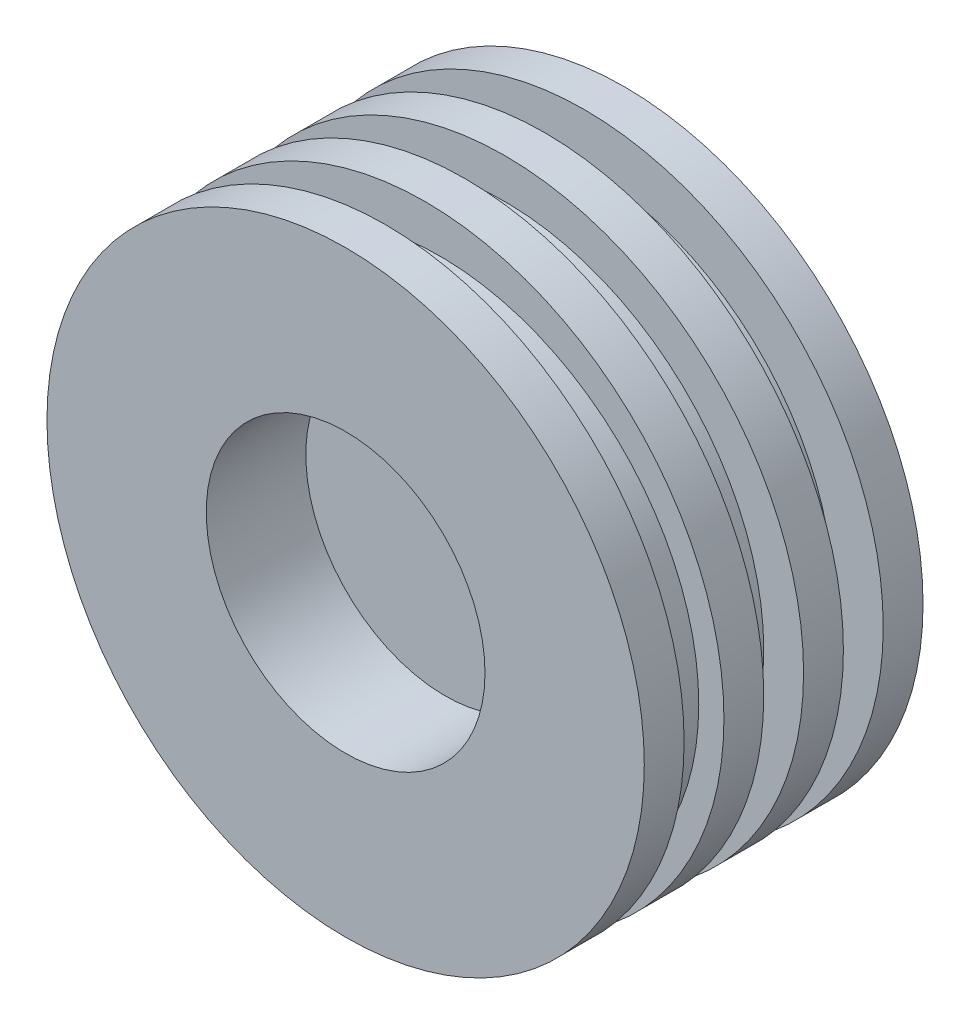
SolidWorks part; units mm, degrees
ref_plane "前视基准面" through (0, 0, 0) normal (0, 0, 1) x (1, 0, 0)
ref_plane "上视基准面" through (0, 0, 0) normal (0, 1, 0) x (1, 0, 0)
ref_plane "右视基准面" through (0, 0, 0) normal (1, 0, 0) x (0, 0, -1)
sketch "草图1" plane through (0, 0, 0) normal (0, 0, 1) x (1, 0, 0)
  circle A0 centre (0, 0) radius 15
  dimension "D1" = 30
extrude "凸台-拉伸1" add sketch "草图1" along normal blind 2
sketch "草图3" plane through (0, 0, 2) normal (0, 0, 1) x (1, 0, 0)
  circle A0 centre (0, 0) radius 12.5
  dimension "D1" = 25
extrude "凸台-拉伸2" add sketch "草图3" along normal blind 2
sketch "草图4" plane through (0, 0, 4) normal (0, 0, 1) x (1, 0, 0)
  circle A0 centre (0, 0) radius 15
extrude "凸台-拉伸3" add sketch "草图4" along normal blind 2
sketch "草图5" plane through (0, 0, 6) normal (0, 0, 1) x (1, 0, 0)
  circle A0 centre (0, 0) radius 13
extrude "凸台-拉伸4" add sketch "草图5" along normal blind 2
sketch "草图6" plane through (0, 0, 8) normal (0, 0, 1) x (1, 0, 0)
  circle A0 centre (0, 0) radius 15
extrude "凸台-拉伸5" add sketch "草图6" along normal blind 2
sketch "草图7" plane through (0, 0, 10) normal (0, 0, 1) x (1, 0, 0)
  circle A0 centre (0.7362, 0) radius 13
extrude "凸台-拉伸6" add sketch "草图7" along normal blind 2
sketch "草图8" plane through (0, 0, 12) normal (0, 0, 1) x (1, 0, 0)
  circle A0 centre (0, 0) radius 15
extrude "凸台-拉伸7" add sketch "草图8" along normal blind 2
sketch "草图9" plane through (0, 0, 14) normal (0, 0, 1) x (1, 0, 0)
  circle A0 centre (0, 0) radius 7
extrude "切除-拉伸1" cut sketch "草图9" against normal blind 5
